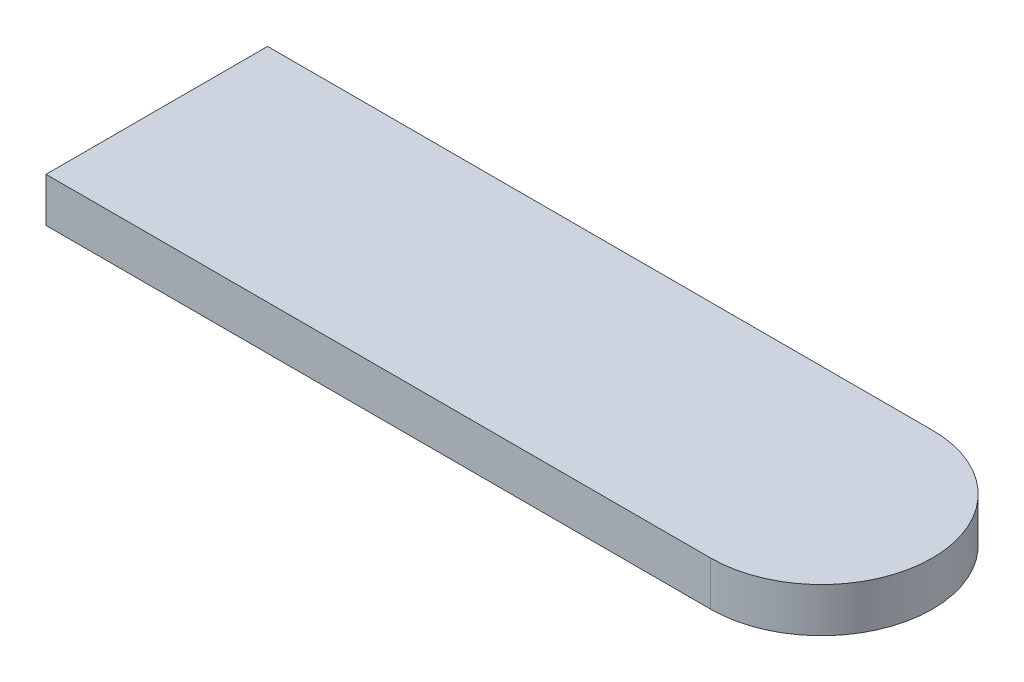
SolidWorks part; units mm, degrees
ref_plane "Plan de face" through (0, 0, 0) normal (0, 0, 1) x (1, 0, 0)
ref_plane "Plan de dessus" through (0, 0, 0) normal (0, 1, 0) x (1, 0, 0)
ref_plane "Plan de droite" through (0, 0, 0) normal (1, 0, 0) x (0, 0, -1)
sketch "Esquisse1" plane through (0, 0, 0) normal (0, 1, 0) x (1, 0, 0)
  line L5 (-87.5, 25) -> (-87.5, -25)
  line L6 (-87.5, -25) -> (87.5, -25) construction
  line L8 (-87.5, -25) -> (-87.5, 25) construction
  line L9 (-87.5, 25) -> (87.5, 25) construction
  line L10 (87.5, -25) -> (87.5, 25) construction
  line L11 (-87.5, -25) -> (87.5, 25) construction
  line L12 (-87.5, 25) -> (87.5, -25) construction
  line L13 (-87.5, -25) -> (62.5, -25)
  line L14 (-87.5, 25) -> (62.5, 25)
  arc A0 (62.5, 25) -> (62.5, -25) centre (62.5, 0) cw
  point P0 (0, 0)
  dimension "D1" = 50
  dimension "D2" = 175
extrude "Boss.-Extru.1" add sketch "Esquisse1" along normal blind 10
